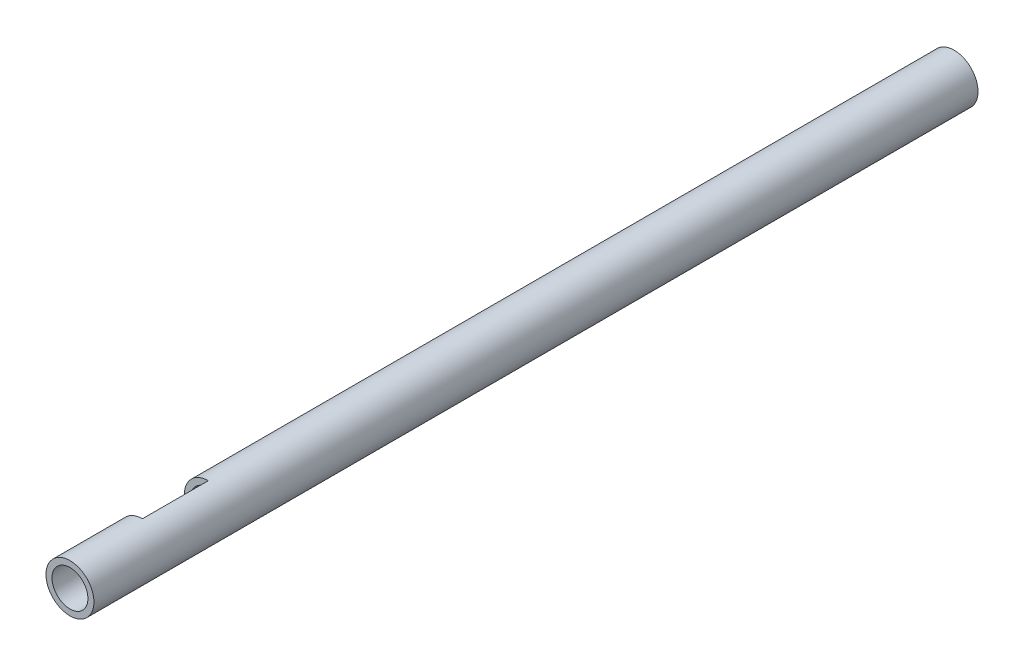
SolidWorks part; units mm, degrees
ref_plane "Front Plane" through (0, 0, 0) normal (0, 0, 1) x (1, 0, 0)
ref_plane "Top Plane" through (0, 0, 0) normal (0, 1, 0) x (1, 0, 0)
ref_plane "Right Plane" through (0, 0, 0) normal (1, 0, 0) x (0, 0, -1)
sketch "Sketch1" plane through (0, 0, 0) normal (1, 0, 0) x (0, 0, -1)
  line L0 (0, 0) -> (-101.6858, 0) construction
  line L2 (0, 20) -> (-738, 20)
  line L3 (0, 20) -> (0, 15)
  line L4 (0, 15) -> (-738, 15)
  line L5 (-738, 20) -> (-738, 15)
  dimension "D1" = 738
  dimension "D2" = 30
  dimension "D3" = 40
revolve "Revolve1" add sketch "Sketch1" angle 360 about L0
sketch "Sketch2" plane through (0, 0, 0) normal (0, 1, 0) x (1, 0, 0)
  line L0 (-37.7148, -650) -> (-87.2485, -650) construction
  line L1 (-37.7148, -707.5) -> (0, -707.5) construction
  line L2 (-37.7148, -707.5) -> (-37.7148, -592.5) construction
  line L3 (-37.7148, -592.5) -> (0, -592.5) construction
  line L4 (0, -707.5) -> (0, -592.5) construction
  line L5 (68, -592.5) -> (20, -592.5) construction
  line L6 (68, -707.5) -> (20, -707.5) construction
  line L7 (-37.7148, -622.5) -> (0, -622.5)
  line L8 (-37.7148, -622.5) -> (-37.7148, -677.5)
  line L9 (-37.7148, -677.5) -> (0, -677.5)
  line L10 (0, -622.5) -> (0, -677.5)
  point P13 (-37.7148, -650)
  dimension "D1" = 55
extrude "Cut-Extrude1" cut sketch "Sketch2" against normal through all and the other way through all
